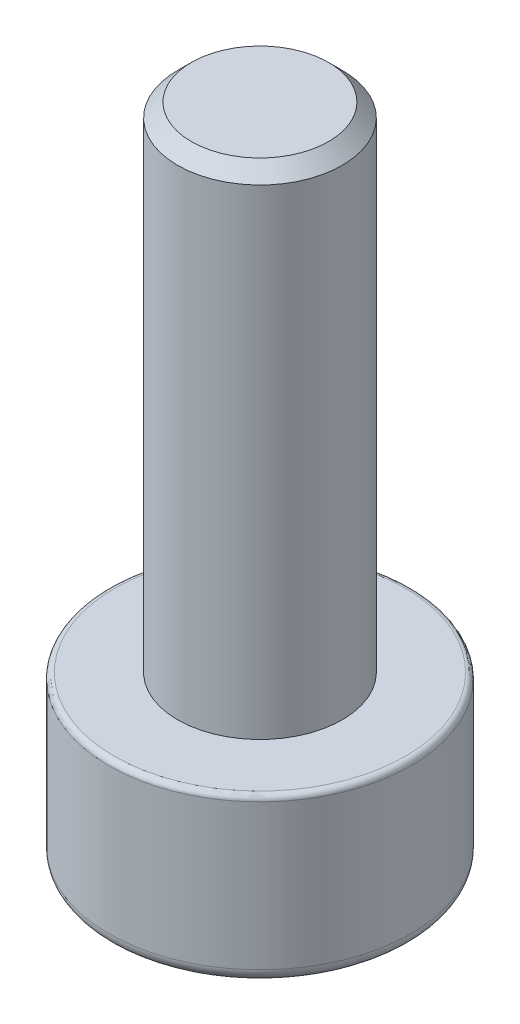
SolidWorks part; units mm, degrees
ref_plane "Front Plane" through (0, 0, 0) normal (0, 0, 1) x (1, 0, 0)
ref_plane "Top Plane" through (0, 0, 0) normal (0, 1, 0) x (1, 0, 0)
ref_plane "Right Plane" through (0, 0, 0) normal (1, 0, 0) x (0, 0, -1)
sketch "Sketch1" plane through (0, 0, 0) normal (0, 1, 0) x (1, 0, 0)
  circle A0 centre (0, 0) radius 2.75
  dimension "D1" = 5.5
extrude "Boss-Extrude1" add sketch "Sketch1" along normal blind 3
sketch "Sketch2" plane through (0, 3, 0) normal (0, 1, 0) x (1, 0, 0)
  circle A0 centre (0, 0) radius 1.5
  dimension "D1" = 3
extrude "Boss-Extrude2" add sketch "Sketch2" along normal blind 9 contours A0
sketch "Sketch3" plane through (0, 0, 0) normal (0, -1, 0) x (1, 0, 0)
  line L1 (0.9342, 0.9746) -> (-0.3769, 1.2963)
  line L2 (-0.3769, 1.2963) -> (-1.3111, 0.3217)
  line L3 (-1.3111, 0.3217) -> (-0.9342, -0.9746)
  line L4 (-0.9342, -0.9746) -> (0.3769, -1.2963)
  line L5 (0.3769, -1.2963) -> (1.3111, -0.3217)
  line L6 (1.3111, -0.3217) -> (0.9342, 0.9746)
  circle A0 centre (0, 0) radius 1.1691 construction
  dimension "D1" = 2.7
extrude "Cut-Extrude1" cut sketch "Sketch3" against normal blind 1.5
chamfer "Chamfer1" distance 0.25 distance2 0.25 6 edges at (-0.2786, 0, -1.1355) (-1.1226, 0, -0.3264) (-0.844, 0, 0.809) (0.2786, 0, 1.1355) (1.1226, 0, 0.3264) (0.844, 0, -0.809)
fillet "Fillet1" radius 0.25 1 edges at (0, 0, 2.75)
chamfer "Chamfer2" distance 0.25 angle 45 1 edges at (0, 12, 1.5)
fillet "Fillet2" radius 0.1 1 edges at (0, 3, 2.75)
